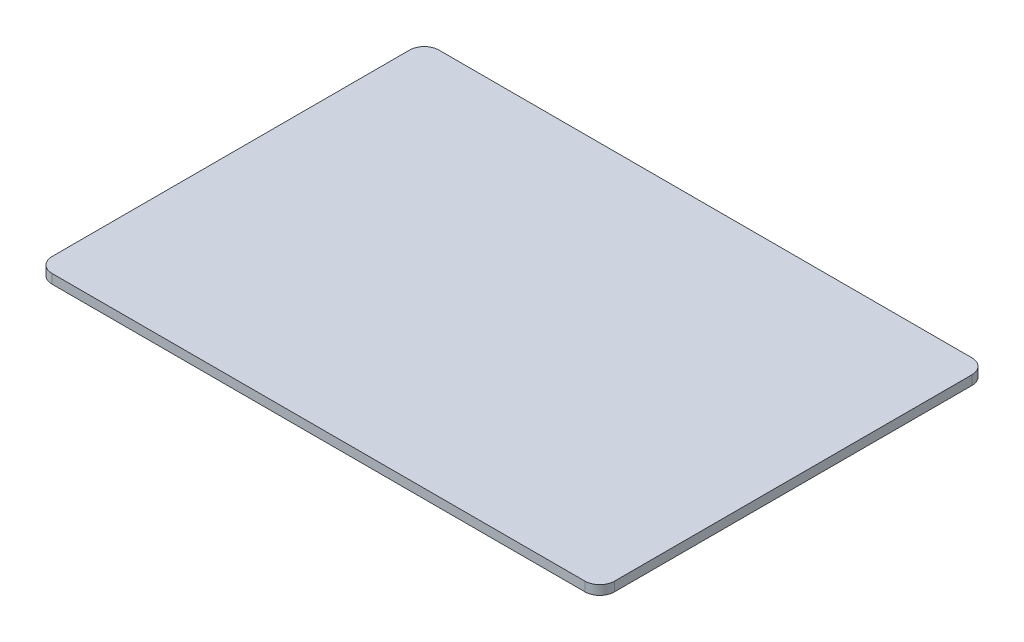
SolidWorks part; units mm, degrees
ref_plane "Front Plane" through (0, 0, 0) normal (0, 0, 1) x (1, 0, 0)
ref_plane "Top Plane" through (0, 0, 0) normal (0, 1, 0) x (1, 0, 0)
ref_plane "Right Plane" through (0, 0, 0) normal (1, 0, 0) x (0, 0, -1)
sketch "Sketch1" plane through (0, 0, 0) normal (0, 1, 0) x (1, 0, 0)
  line L1 (-181.65, -131.85) -> (181.65, -131.85)
  line L2 (-191.65, -121.85) -> (-191.65, 121.85)
  line L3 (-181.65, 131.85) -> (181.65, 131.85)
  line L4 (191.65, -121.85) -> (191.65, 121.85)
  line L5 (-191.65, -131.85) -> (191.65, 131.85) construction
  line L6 (-191.65, 131.85) -> (191.65, -131.85) construction
  arc A0 (-191.65, 121.85) -> (-181.65, 131.85) centre (-181.65, 121.85) cw
  arc A1 (-181.65, -131.85) -> (-191.65, -121.85) centre (-181.65, -121.85) cw
  arc A2 (191.65, -121.85) -> (181.65, -131.85) centre (181.65, -121.85) cw
  arc A3 (181.65, 131.85) -> (191.65, 121.85) centre (181.65, 121.85) cw
  point P0 (0, 0)
  dimension "D3" = 10
  dimension "D4" = 10
  dimension "D5" = 10
  dimension "D6" = 10
  dimension "D1" = 263.7
  dimension "D2" = 383.3
extrude "Boss-Extrude1" add sketch "Sketch1" along normal blind 6.35
